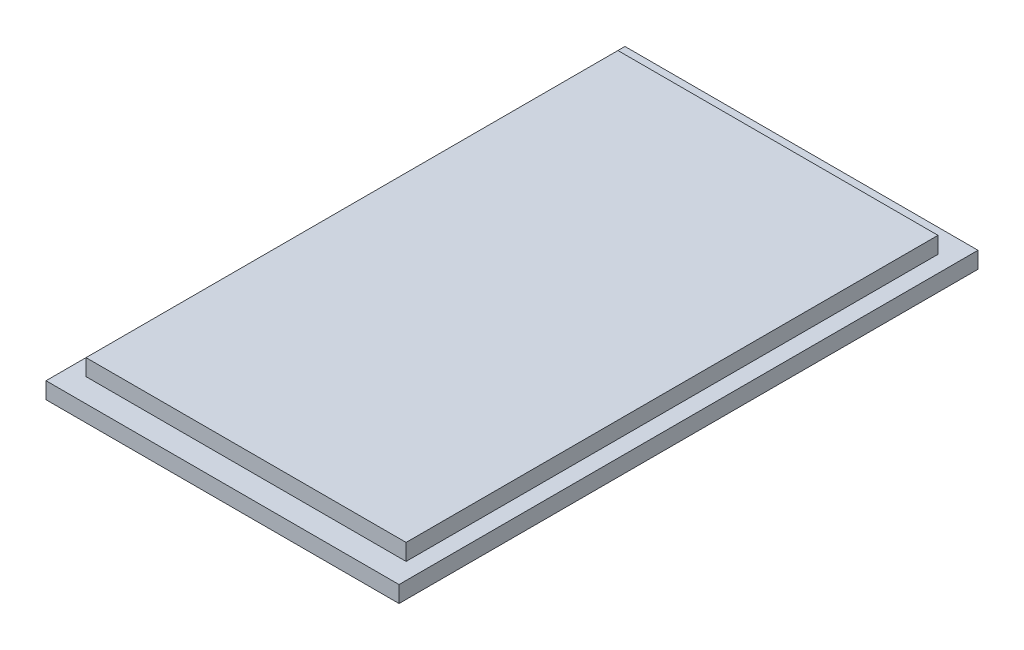
SolidWorks part; units mm, degrees
ref_plane "Front Plane" through (0, 0, 0) normal (0, 0, 1) x (1, 0, 0)
ref_plane "Top Plane" through (0, 0, 0) normal (0, 1, 0) x (1, 0, 0)
ref_plane "Right Plane" through (0, 0, 0) normal (1, 0, 0) x (0, 0, -1)
sketch "Sketch1" plane through (0, 0, 0) normal (0, 1, 0) x (1, 0, 0)
  line L1 (-175.6426, -124.0686) -> (-138.1426, -124.0686)
  line L2 (-175.6426, -124.0686) -> (-175.6426, -62.5686)
  line L3 (-175.6426, -62.5686) -> (-138.1426, -62.5686)
  line L4 (-138.1426, -124.0686) -> (-138.1426, -62.5686)
  dimension "D1" = 61.5
  dimension "D2" = 37.5
extrude "Boss-Extrude1" add sketch "Sketch1" along normal blind 1.75
sketch "Sketch2" plane through (0, 1.75, 0) normal (0, 1, 0) x (1, 0, 0)
  line L0 (-138.1426, -124.0686) -> (-138.1426, -62.5686) construction
  line L1 (-173.8926, -121.5686) -> (-139.8926, -121.5686)
  line L2 (-173.8926, -121.5686) -> (-173.8926, -65.0686)
  line L3 (-173.8926, -65.0686) -> (-139.8926, -65.0686)
  line L4 (-139.8926, -121.5686) -> (-139.8926, -65.0686)
  line L6 (-175.6426, -124.0686) -> (-138.1426, -124.0686) construction
  dimension "D1" = 56.5
  dimension "D2" = 34
  dimension "D3" = 1.75
  dimension "D4" = 2.5
extrude "Boss-Extrude2" add sketch "Sketch2" along normal blind 1.75
